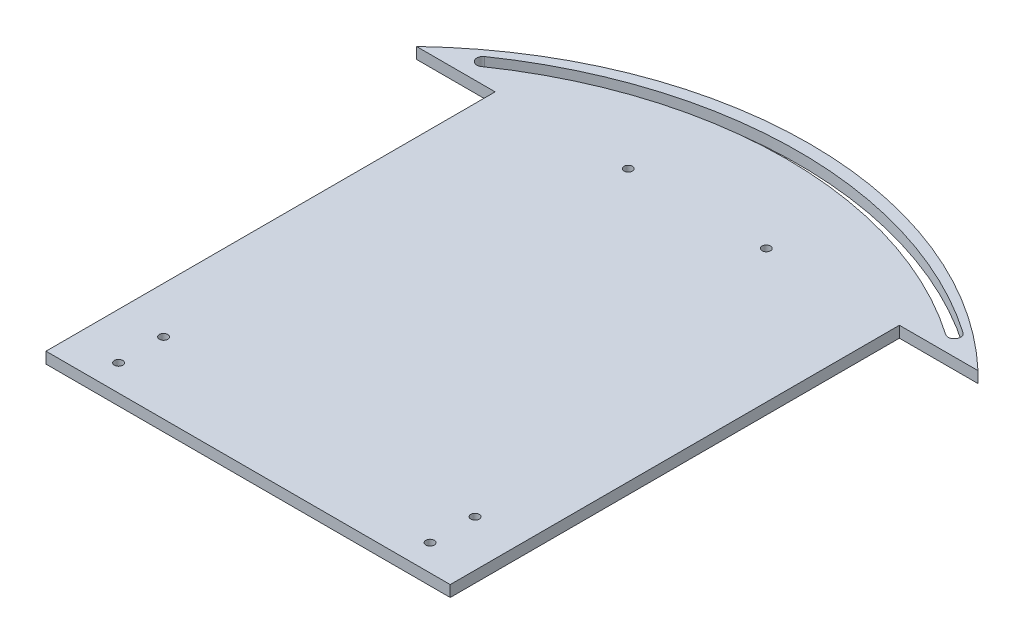
SolidWorks part; units mm, degrees
ref_plane "Front Plane" through (0, 0, 0) normal (0, 0, 1) x (1, 0, 0)
ref_plane "Top Plane" through (0, 0, 0) normal (0, 1, 0) x (1, 0, 0)
ref_plane "Right Plane" through (0, 0, 0) normal (1, 0, 0) x (0, 0, -1)
sketch "Esquisse2" plane through (0, 0, 0) normal (0, 1, 0) x (1, 0, 0)
  line L0 (0, 0) -> (28, 0)
  line L16 (172, 0) -> (200, 0)
  line L17 (28, 0) -> (28, -160)
  line L18 (28, -160) -> (172, -160)
  line L19 (172, -160) -> (172, 0)
  line L20 (100, -160) -> (100, 49.6487) construction
  arc A0 (0, 0) -> (200, 0) centre (100, -105) cw
  circle A1 centre (44.52, -134.6458) radius 1.5
  circle A2 centre (44.52, -150.6684) radius 1.5
  circle A3 centre (155.48, -150.6684) radius 1.5
  circle A4 centre (155.48, -134.6458) radius 1.5
  circle A5 centre (75.4124, 0) radius 1.5
  circle A6 centre (124.5876, 0) radius 1.5
  arc A7 (16.4998, 7.1977) -> (184.3914, 7.1977) centre (100.4456, -113.9796) cw construction
  arc A8 (185.6575, 9.0255) -> (15.2336, 9.0255) centre (100.4456, -113.9796) ccw
  arc A9 (183.1252, 5.37) -> (17.766, 5.37) centre (100.4456, -113.9796) ccw
  arc A10 (183.1252, 5.37) -> (185.6575, 9.0255) centre (184.3914, 7.1977) ccw
  arc A11 (15.2336, 9.0255) -> (17.766, 5.37) centre (16.4998, 7.1977) ccw
  point P3 (100, 40)
  point P25 (100.4456, 33.4342)
  dimension "D6" = 3
  dimension "D7" = 3
  dimension "D2" = 28
  dimension "D3" = 28
  dimension "D4" = 160
  dimension "D5" = 200
  dimension "D12" = 200
extrude "Boss.-Extru.1" add sketch "Esquisse2" along normal blind 4
